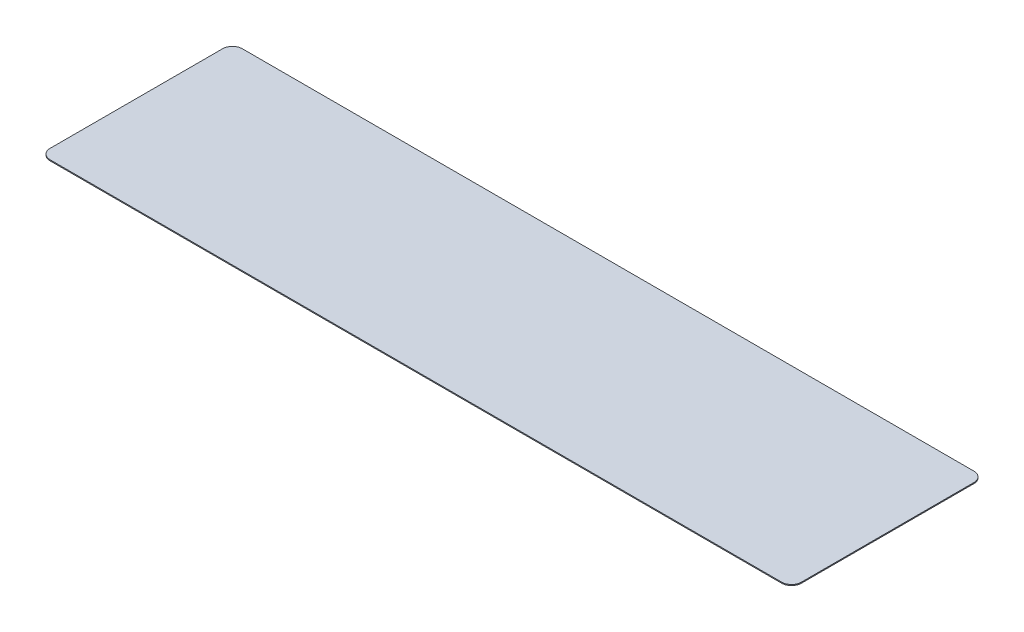
SolidWorks part; units mm, degrees
ref_plane "Спереди" through (0, 0, 0) normal (0, 0, 1) x (1, 0, 0)
ref_plane "Сверху" through (0, 0, 0) normal (0, 1, 0) x (1, 0, 0)
ref_plane "Справа" through (0, 0, 0) normal (1, 0, 0) x (0, 0, -1)
sketch "Эскиз2" plane through (0, 0, 0) normal (0, 1, 0) x (1, 0, 0)
  line L1 (74.2, -19.5) -> (-74.2, -19.5)
  line L2 (76.2, -17.5) -> (76.2, 17.5)
  line L3 (74.2, 19.5) -> (-74.2, 19.5)
  line L4 (-76.2, -17.5) -> (-76.2, 17.5)
  line L5 (76.2, -19.5) -> (-76.2, 19.5) construction
  line L6 (76.2, 19.5) -> (-76.2, -19.5) construction
  arc A0 (74.2, -19.5) -> (76.2, -17.5) centre (74.2, -17.5) ccw
  arc A1 (76.2, 17.5) -> (74.2, 19.5) centre (74.2, 17.5) ccw
  arc A2 (-74.2, -19.5) -> (-76.2, -17.5) centre (-74.2, -17.5) cw
  arc A3 (-74.2, 19.5) -> (-76.2, 17.5) centre (-74.2, 17.5) ccw
  point P0 (0, 0)
  dimension "D3" = 2
  dimension "D1" = 39
  dimension "D2" = 152.4
extrude "Бобышка-Вытянуть1" add sketch "Эскиз2" along normal blind 0.2
